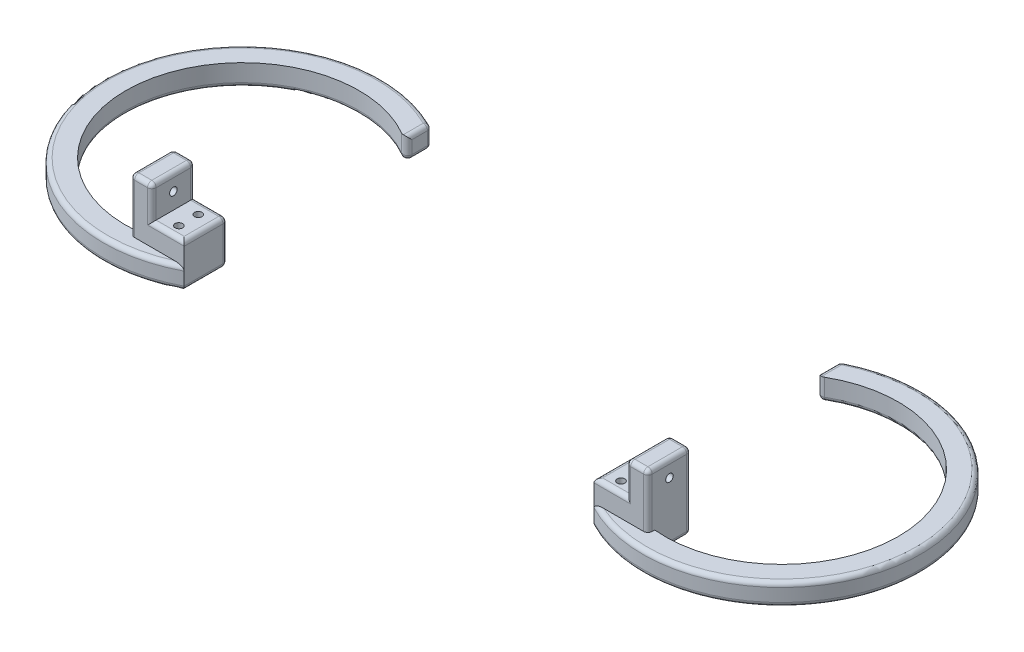
SolidWorks part; units mm, degrees
ref_plane "Front Plane" through (0, 0, 0) normal (0, 0, 1) x (1, 0, 0)
ref_plane "Top Plane" through (0, 0, 0) normal (0, 1, 0) x (1, 0, 0)
ref_plane "Right Plane" through (0, 0, 0) normal (1, 0, 0) x (0, 0, -1)
sketch "Sketch1" plane through (0, 0, 0) normal (0, 1, 0) x (1, 0, 0)
  line L0 (0, 0) -> (-20, 0) construction
  line L1 (-20, 0) -> (-20, 45) construction
  line L2 (-20, 0) -> (-20, -45) construction
  line L3 (-20, 45) -> (-20, 57)
  line L4 (-20, -45) -> (-20, -57)
  arc A0 (-20, 45) -> (-20, -45) centre (10, 0) cw
  arc A1 (-20, 57) -> (-20, -57) centre (10, 0) cw
  dimension "D5" = 0
  dimension "D1" = 30
  dimension "D2" = 45
  dimension "D3" = 12
  dimension "D4" = 12
extrude "Boss-Extrude1" add sketch "Sketch1" against normal blind 10
sketch "Sketch2" plane through (-20, 0, 0) normal (-1, 0, 0) x (0, 0, 1)
  line L1 (57, -10) -> (37, -10)
  line L2 (57, -10) -> (57, 0)
  line L3 (57, 0) -> (37, 0)
  line L4 (37, -10) -> (37, 0)
  dimension "D1" = 20
extrude "Boss-Extrude2" add sketch "Sketch2" against normal blind 15
sketch "Sketch3" plane through (-5, 0, 0) normal (1, 0, 0) x (0, 0, -1)
  line L3 (-37, 0) -> (-57, 0)
  line L4 (-37, 0) -> (-37, 15)
  line L5 (-37, 15) -> (-57, 15)
  line L6 (-57, 0) -> (-57, 15)
  dimension "D1" = 15
  dimension "D2" = 20
extrude "Boss-Extrude10" add sketch "Sketch3" along normal blind 10 separate body
sketch "Sketch4" plane through (0, 0, 0) normal (0, -1, 0) x (-1, 0, 0)
  line L1 (5, -37) -> (-5, -37)
  line L2 (5, -37) -> (5, -57)
  line L3 (5, -57) -> (-5, -57)
  line L4 (-5, -37) -> (-5, -57)
extrude "Boss-Extrude11" add sketch "Sketch4" along normal blind 10
ref_plane "Plane1" through (0, 15, 0) normal (0, 1, 0) x (1, 0, 0)
ref_plane "Plane2" through (-5, 0, 0) normal (-1, 0, 0) x (0, 0, 1)
ref_plane "Plane3" through (-30, 0, 0) normal (-1, 0, 0) x (0, 0, 1)
sketch "Sketch10" plane through (0, 0, 0) normal (0, 1, 0) x (1, 0, 0)
  line L1 (-20, -37) -> (-5, -37)
  line L2 (-20, -37) -> (-20, -57)
  line L3 (-20, -57) -> (-5, -57)
  line L4 (-5, -37) -> (-5, -57)
sketch "Sketch12" plane through (0, 15, 0) normal (0, 1, 0) x (1, 0, 0)
  line L1 (5, -37) -> (-5, -37)
  line L2 (5, -37) -> (5, -57)
  line L3 (5, -57) -> (-5, -57)
  line L4 (-5, -37) -> (-5, -57)
extrude "Boss-Extrude16" add sketch "Sketch12" along normal blind 10
extrude "Boss-Extrude17" add sketch "Sketch10" along normal blind 10
sketch "Sketch14" plane through (0, 10, 0) normal (0, 1, 0) x (1, 0, 0)
  line L0 (-20, -57) -> (-5, -57) construction
  line L1 (-5, -57) -> (-5, -37) construction
  circle A0 centre (-12.5, -43) radius 1.75
  circle A1 centre (-12.5, -52) radius 1.75
  dimension "D1" = 3.5
  dimension "D2" = 3.5
  dimension "D4" = 5
  dimension "D5" = 7.5
  dimension "D3" = 9
extrude "Cut-Extrude1" cut sketch "Sketch14" against normal up to next
sketch "Sketch15" plane through (-5, 0, 0) normal (-1, 0, 0) x (0, 0, 1)
  line L1 (37, 10) -> (37, 25) construction
  line L2 (37, 10) -> (57, 10) construction
  circle A0 centre (47, 17.5) radius 1.75
  dimension "D1" = 10
  dimension "D2" = 3.5
  dimension "D3" = 7.5
extrude "Cut-Extrude2" cut sketch "Sketch15" against normal up to next
fillet "Fillet1" radius 2 22 edges at (-7.5, -10, 37) (5, 7.5, 37) (0, 25, 37) (-5, 17.5, 37) (-12.5, 10, 37) (-20, 0, 37) (-5, 17.5, 57) (-12.5, 10, 57) (-5, 25, 47) (5, 25, 47) (0, 25, 57) (5, 12.5, 57) (-20, 0, -51) (-20, -5, -45) (-20, -10, -51) (-20, -5, -57) (74.4127, 0, 0) (-20, 10, 47) (-20, -10, 47) (5, -10, 45.4258) (62.4325, -10, -13.2604) (74.4127, -10, 0)
ref_plane "Plane4" through (-115, 0, 0) normal (-1, 0, 0) x (0, 0, 1)
mirror "Mirror2" about plane through (-115, 0, 0) normal (-1, 0, 0) of bodies 115
